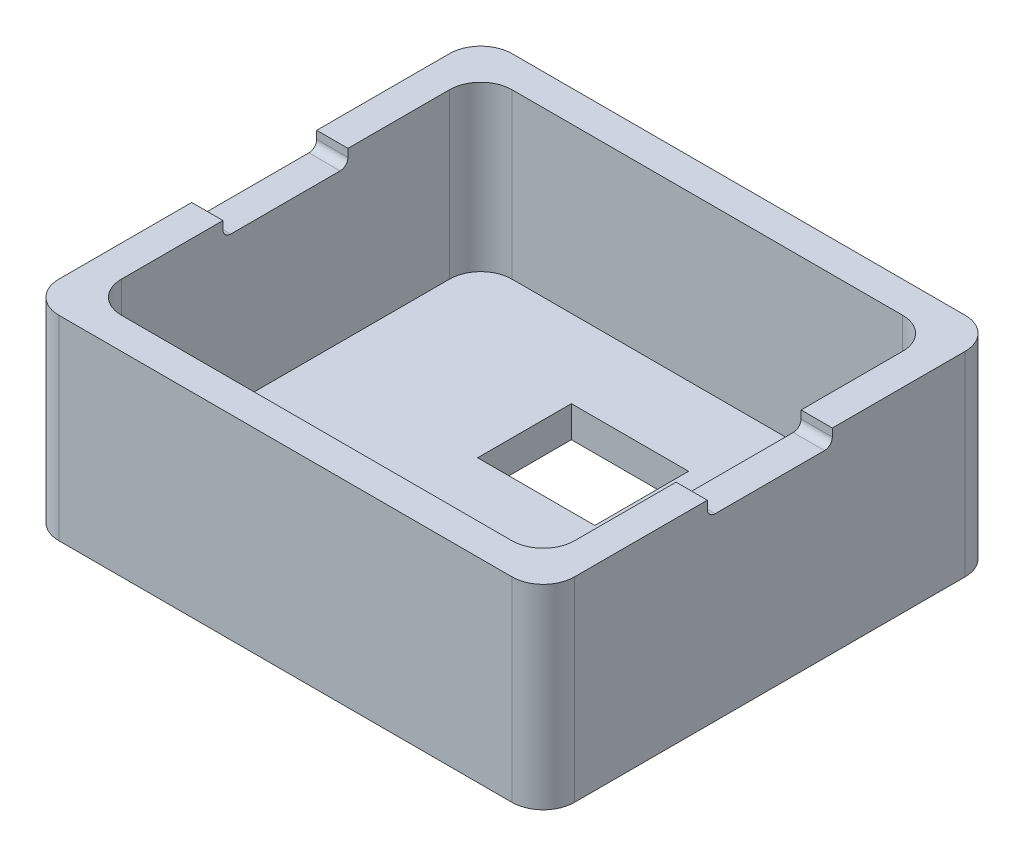
SolidWorks part; units mm, degrees
ref_plane "Front Plane" through (0, 0, 0) normal (0, 0, 1) x (1, 0, 0)
ref_plane "Top Plane" through (0, 0, 0) normal (0, 1, 0) x (1, 0, 0)
ref_plane "Right Plane" through (0, 0, 0) normal (1, 0, 0) x (0, 0, -1)
sketch "Sketch1" plane through (0, 0, 0) normal (0, 1, 0) x (1, 0, 0)
  line L1 (-16.5, -14.5) -> (16.5, -14.5)
  line L2 (-16.5, -14.5) -> (-16.5, 14.5)
  line L3 (-16.5, 14.5) -> (16.5, 14.5)
  line L4 (16.5, -14.5) -> (16.5, 14.5)
  line L5 (-16.5, -14.5) -> (16.5, 14.5) construction
  line L6 (-16.5, 14.5) -> (16.5, -14.5) construction
  point P0 (0, 0)
  dimension "D1" = 33
  dimension "D2" = 29
extrude "Boss-Extrude1" add sketch "Sketch1" along normal blind 2
sketch "Sketch2" plane through (0, 2, 0) normal (0, 1, 0) x (1, 0, 0)
  line L1 (-14.5, -12.5) -> (14.5, -12.5)
  line L2 (-14.5, -12.5) -> (-14.5, 12.5)
  line L3 (-14.5, 12.5) -> (14.5, 12.5)
  line L4 (14.5, -12.5) -> (14.5, 12.5)
  line L5 (-14.5, -12.5) -> (14.5, 12.5) construction
  line L6 (-14.5, 12.5) -> (14.5, -12.5) construction
  line L7 (-16.5, -14.5) -> (16.5, -14.5)
  line L8 (-16.5, -14.5) -> (-16.5, 14.5)
  line L9 (-16.5, 14.5) -> (16.5, 14.5)
  line L10 (16.5, -14.5) -> (16.5, 14.5)
  line L11 (-16.5, -14.5) -> (16.5, 14.5) construction
  line L12 (-16.5, 14.5) -> (16.5, -14.5) construction
  point P0 (0, 0)
  point P6 (0, 0)
  dimension "D1" = 2
  dimension "D2" = 2
extrude "Boss-Extrude2" add sketch "Sketch2" along normal blind 10.5
sketch "Sketch4" plane through (0, 2, 0) normal (0, 1, 0) x (1, 0, 0)
  line L1 (-3.7, 1.5) -> (3.8, 1.5)
  line L2 (-3.7, 1.5) -> (-3.7, 7.5)
  line L3 (-3.7, 7.5) -> (3.8, 7.5)
  line L4 (3.8, 1.5) -> (3.8, 7.5)
  line L5 (-3.7, 1.5) -> (3.8, 7.5) construction
  line L6 (-3.7, 7.5) -> (3.8, 1.5) construction
  line L8 (14.5, 12.5) -> (-14.5, 12.5) construction
  line L13 (-14.5, 12.5) -> (-14.5, -12.5) construction
  point P0 (0.05, 4.5)
  dimension "D1" = 5
  dimension "D2" = 6
  dimension "D3" = 7.5
  dimension "D4" = 10.8
extrude "Cut-Extrude1" cut sketch "Sketch4" against normal up to surface (2 mm away) up to face at (0, 0, 0)
fillet "Fillet1" radius 2 8 edges at (-14.5, 7.25, -12.5) (14.5, 7.25, -12.5) (14.5, 7.25, 12.5) (-14.5, 7.25, 12.5) (-16.5, 6.25, -14.5) (16.5, 6.25, -14.5) (16.5, 6.25, 14.5) (-16.5, 6.25, 14.5)
sketch "Sketch5" plane through (16.5, 0, 0) normal (1, 0, 0) x (0, 0, -1)
  line L0 (0, 12.5) -> (0, 0) construction
  line L1 (-12.5, 12.5) -> (12.5, 12.5) construction
  line L3 (-4, 11.5) -> (4, 11.5)
  line L4 (-4, 11.5) -> (-4, 12.5)
  line L5 (-4, 12.5) -> (4, 12.5)
  line L6 (4, 11.5) -> (4, 12.5)
  line L7 (-4, 11.5) -> (4, 12.5) construction
  line L8 (-4, 12.5) -> (4, 11.5) construction
  point P5 (0, 12)
  dimension "D1" = 1
  dimension "D2" = 8
extrude "Cut-Extrude2" cut sketch "Sketch5" against normal up to surface (31 mm away)
fillet "Fillet2" radius 0.5 2 edges at (15.5, 11.5, -4) (15.5, 11.5, 4)
mirror "Mirror1" about plane through (0, 0, 0) normal (1, 0, 0) of "Cut-Extrude2", "Fillet2"
